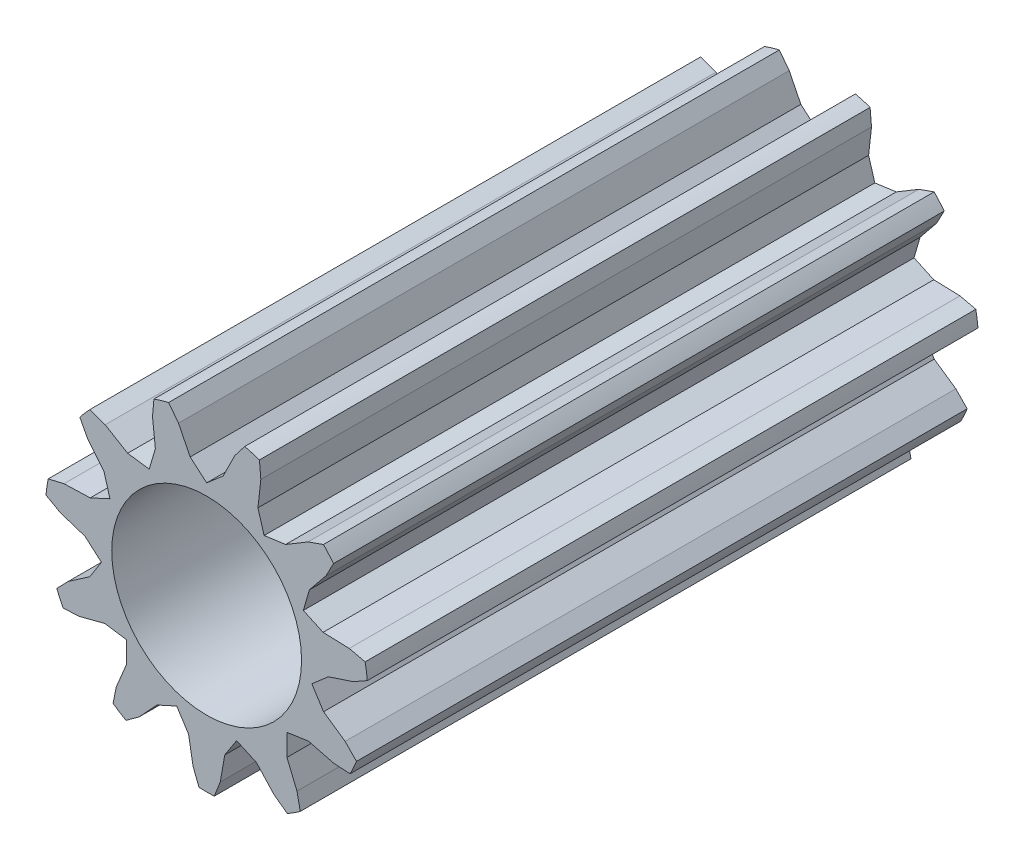
SolidWorks part; units mm, degrees
ref_plane "Front Plane" through (0, 0, 0) normal (0, 0, 1) x (1, 0, 0)
ref_plane "Top Plane" through (0, 0, 0) normal (0, 1, 0) x (1, 0, 0)
ref_plane "Right Plane" through (0, 0, 0) normal (1, 0, 0) x (0, 0, -1)
sketch "Sketch1" plane through (0, 0, 0) normal (0, 0, 1) x (1, 0, 0)
  line L1 (4.0659, -4.0659) -> (-4.0659, -4.0659) construction
  line L2 (4.0659, -4.0659) -> (4.0659, 4.0659) construction
  line L3 (4.0659, 4.0659) -> (-4.0659, 4.0659) construction
  line L4 (-4.0659, -4.0659) -> (-4.0659, 4.0659) construction
  line L5 (4.0659, -4.0659) -> (-4.0659, 4.0659) construction
  line L6 (4.0659, 4.0659) -> (-4.0659, -4.0659) construction
  circle A0 centre (0, 0) radius 9.7778
  circle A1 centre (0, 0) radius 5.75 construction
  dimension "D1" = 19.5556
  dimension "D2" = 11.5
extrude "Boss-Extrude1" add sketch "Sketch1" along normal blind 37
sketch "Sketch2" plane through (0, 0, 0) normal (0, 0, 1) x (1, 0, 0)
  line L0 (0, 0) -> (0, 10.088) construction
  line L1 (0, 6.4402) -> (-0.9985, 7.2997)
  line L8 (-1.7043, 10.285) -> (0, 10.9993)
  line L11 (-0.9985, 7.2997) -> (-1.7043, 8.7207)
  line L12 (-1.7043, 8.7207) -> (-2.3066, 9.5018)
  line L13 (-2.3066, 9.5018) -> (-1.7043, 10.285)
  line L14 (2.3066, 9.5018) -> (1.7043, 10.285)
  line L15 (1.7043, 8.7207) -> (2.3066, 9.5018)
  line L16 (0.9985, 7.2997) -> (1.7043, 8.7207)
  line L17 (1.7043, 10.285) -> (0, 10.9993)
  line L18 (0, 6.4402) -> (0.9985, 7.2997)
  circle A14 centre (0, 0) radius 9.7778 construction
  point P16 (0, 9.7778)
  dimension "D5" = 0.6023
  dimension "D6" = 0.7811
  dimension "D1" = 0.9985
  dimension "D2" = 0.8594
  dimension "D3" = 0.7058
  dimension "D4" = 1.4211
  dimension "D7" = 0.7832
  dimension "D8" = 0.6023
  dimension "D9" = 0.7142
  dimension "D10" = 1.7043
extrude "Cut-Extrude1" cut sketch "Sketch2" along normal through all
sketch "Sketch3" plane through (0, 0, 0) normal (0, 0, 1) x (1, 0, 0)
  circle A0 centre (0, 0) radius 7.5
  dimension "D1" = 15
sketch "Sketch4" plane through (0, 0, 37) normal (0, 0, 1) x (1, 0, 0)
  circle A0 centre (0, 0) radius 5.75
  dimension "D1" = 11.5
extrude "Cut-Extrude2" cut sketch "Sketch4" against normal through all both and the other way through all
pattern_circular "CirPattern1" count 11 over 360 about axis through (0, 0, 0) along (0, 0, 1) of "Cut-Extrude1"
sketch "Sketch5" plane through (0, 0, 0) normal (0, 0, 1) x (1, 0, 0)
  line L0 (0, 0) -> (0, 16.5734) construction
  arc A0 (0, 2.7703) -> (-2.7395, 5.5802) centre (3.9333, 9.3453) cw
  arc A1 (-2.7395, 5.5802) -> (0, 7.0858) centre (3.4783, -2.4876) cw
  arc A2 (2.7395, 5.5802) -> (0, 7.0858) centre (-3.4783, -2.4876) ccw
  arc A3 (0, 2.7703) -> (2.7395, 5.5802) centre (-3.9333, 9.3453) ccw
equation "\"circle\"=19.5556"
equation "\"D1@Sketch1\"=\"circle\""
equation "\"separator_width\"=45"
equation "\"big-gear-thiccness\"=2"
equation "\"D1@Boss-Extrude1\"=\"separator_width\" - \"big-gear-thiccness\"-10/2+2-3"
